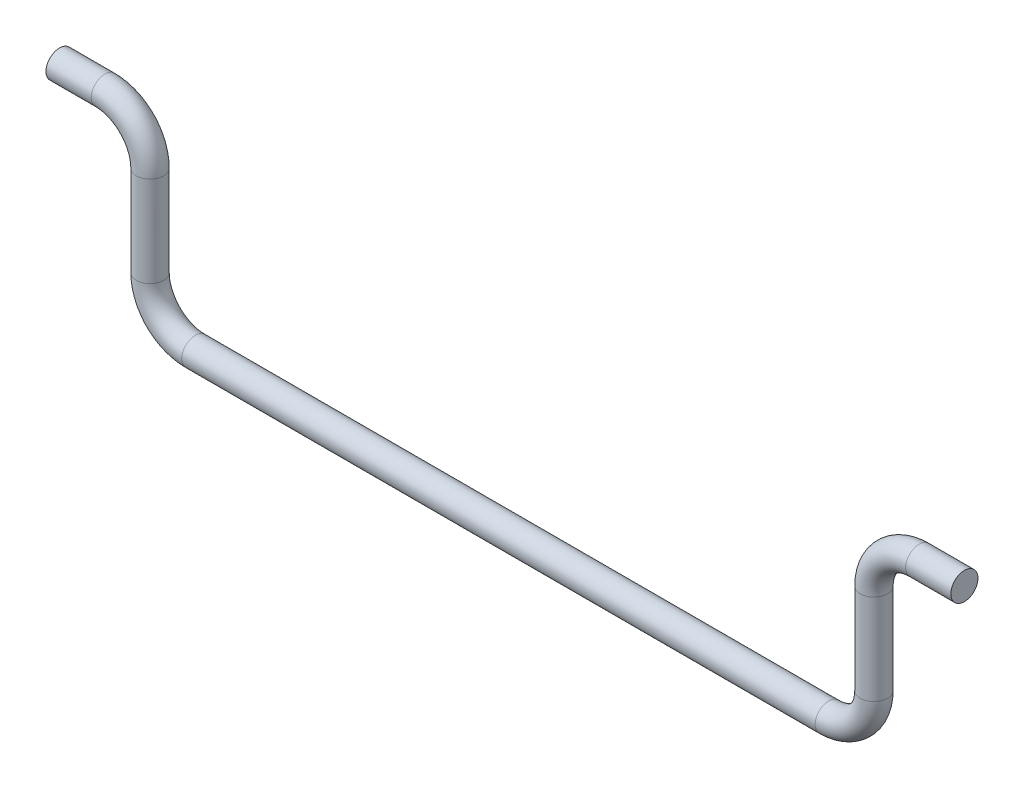
SolidWorks part; units mm, degrees
material "AISI 304"
ref_plane "Front Plane" through (0, 0, 0) normal (0, 0, 1) x (1, 0, 0)
ref_plane "Top Plane" through (0, 0, 0) normal (0, 1, 0) x (1, 0, 0)
ref_plane "Right Plane" through (0, 0, 0) normal (1, 0, 0) x (0, 0, -1)
sketch "Sketch1" plane through (0, 0, 0) normal (0, 0, 1) x (1, 0, 0)
  line L0 (0, 0) -> (2, 0)
  line L1 (4, -2) -> (4, -6)
  line L2 (6, -8) -> (34, -8)
  line L3 (36, -6) -> (36, -2)
  line L4 (38, 0) -> (40, 0)
  arc A0 (36, -2) -> (38, 0) centre (38, -2) cw
  arc A1 (34, -8) -> (36, -6) centre (34, -6) ccw
  arc A2 (4, -6) -> (6, -8) centre (6, -6) ccw
  arc A3 (2, 0) -> (4, -2) centre (2, -2) cw
  point P11 (36, -8)
  point P14 (4, -8)
  point P17 (4, 0)
  dimension "D4" = 2
  dimension "D1" = 32
  dimension "D2" = 8
  dimension "D3" = 4
sketch "Sketch2" plane through (0, 0, 0) normal (1, 0, 0) x (0, 0, -1)
  circle A0 centre (0, 0) radius 0.6
  dimension "D1" = 1.2
sweep "Sweep1" add profiles "Sketch2" path "Sketch1"
